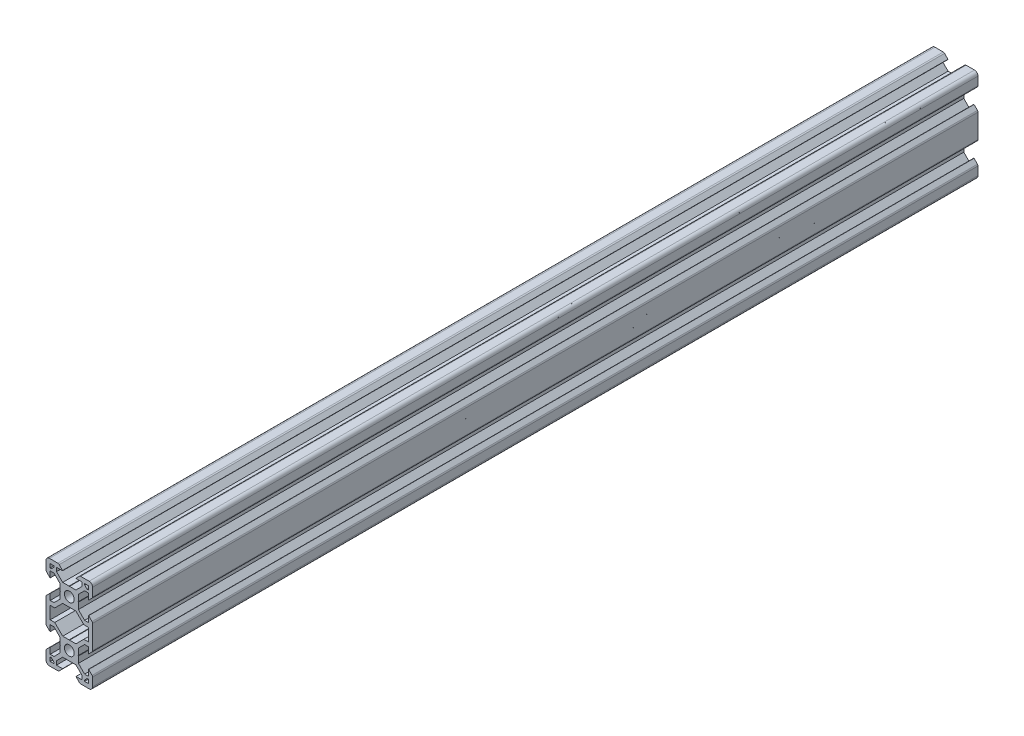
SolidWorks part; units mm, degrees
ref_plane "Front Plane" through (0, 0, 0) normal (0, 0, 1) x (1, 0, 0)
ref_plane "Top Plane" through (0, 0, 0) normal (0, 1, 0) x (1, 0, 0)
ref_plane "Right Plane" through (0, 0, 0) normal (1, 0, 0) x (0, 0, -1)
sketch "Sketch1" plane through (0, 0, 0) normal (0, 0, 1) x (1, 0, 0)
  line L0 (-8.2, 2.8875) -> (-8.2, 5.4975)
  line L3 (-4.9072, 9.9975) -> (-8.5, 9.9975)
  line L4 (-10, 4.9047) -> (-10, 8.4975)
  line L5 (-2.1, 0) -> (-3.8, 0) construction
  line L6 (0, 3.8) -> (0, 0) construction
  line L7 (-0.1, 3.9) -> (-2.8404, 3.9)
  line L8 (-3.9, 0.1) -> (-3.9, 2.8383)
  line L9 (-2.89, 8.1975) -> (-5.5, 8.1975)
  line L10 (-6.57, 8.1975) -> (-6.57, 7.6575)
  line L11 (-8.2, 6.5675) -> (-7.66, 6.5675)
  line L12 (-5.5, 8.1975) -> (-5.5, 6.5588)
  line L13 (-6.56, 5.4975) -> (-8.2, 5.4975)
  line L14 (-8.2, 8.1975) -> (-1.4852, 1.4847) construction
  line L15 (-6.56, 5.4975) -> (-3.9, 2.8383)
  line L16 (-5.5, 6.5588) -> (-2.8404, 3.9)
  line L17 (-7.66, 6.5675) -> (-6.57, 7.6575)
  line L18 (-8.7302, 7.6671) -> (-0.5302, -0.5304) construction
  line L19 (-7.6698, 8.7279) -> (0.5302, 0.5304) construction
  line L20 (-8.2, 8.1975) -> (0, 0) construction
  line L21 (-8.2, 6.5675) -> (-8.2, 8.1975)
  line L22 (-8.2, -0.0025) -> (-8.2, 8.1975) construction
  line L23 (-6.57, 8.1975) -> (-8.2, 8.1975)
  line L24 (0, 8.1975) -> (-8.2, 8.1975) construction
  line L25 (-10, -0.0025) -> (-10, 9.9975) construction
  line L26 (0, 9.9975) -> (-10, 9.9975) construction
  line L27 (-2.89, 8.3075) -> (-2.89, 8.1975)
  line L29 (-8.31, 2.8875) -> (-8.2, 2.8875)
  line L30 (-4.3486, 9.7661) -> (-2.89, 8.3075)
  line L31 (-8.31, 2.8875) -> (-9.7686, 4.3461)
  line L34 (-0.1, 3.9) -> (0, 3.8)
  line L35 (-3.9, 0.1) -> (-3.8, 0)
  line L36 (-8.2, -7.2996) -> (-6.24, -7.2996)
  line L37 (0, 0) -> (0, -10) construction
  line L38 (-0.1, -3.9) -> (-2.8404, -3.9)
  line L39 (-3.8, 0) -> (-3.9, -0.1)
  line L40 (-3.9, -0.1) -> (-3.9, -2.84)
  line L41 (-2.8404, -3.9) -> (-6.24, -7.2996)
  line L42 (-3.9, -2.84) -> (-6.56, -5.5)
  line L43 (-8.2, -2.89) -> (-8.2, -5.5)
  line L44 (-6.56, 5.4975) -> (-6.56, -5.5) construction
  line L45 (-6.56, -5.5) -> (-8.2, -5.5)
  line L46 (-0.1, -3.9) -> (0, -3.8)
  line L48 (-8.2, -2.89) -> (-8.31, -2.89)
  line L49 (-8.31, -2.89) -> (-9.7657, -4.3457)
  line L52 (-10, -10) -> (0, -10) construction
  line L53 (-8.2, -7.2996) -> (-8.2, -10)
  line L61 (-10, -4.9114) -> (-10, -10)
  arc A1 (-10, 8.4975) -> (-8.5, 9.9975) centre (-8.5, 8.4975) cw
  arc A2 (-9.7686, 4.3461) -> (-10, 4.9047) centre (-9.21, 4.9047) cw
  arc A3 (-4.3486, 9.7661) -> (-4.9072, 9.9975) centre (-4.9072, 9.2075) ccw
  arc A4 (-9.7657, -4.3457) -> (-10, -4.9114) centre (-9.2, -4.9114) ccw
  arc A6 (0, 2.1) -> (0, -2.1) centre (0, 0) ccw
  point P29 (-10, 9.9975)
  point P39 (-10, 4.5775)
  point P42 (-4.58, 9.9975)
  point P48 (-10, -4.58)
  dimension "D15" = 1.5
  dimension "D22" = 0.79
  dimension "D30" = 1.96
  dimension "D31" = 2.1
  dimension "D39" = 0.8
  dimension "D4" = 1.8
  dimension "D5" = 3.43
  dimension "D6" = 3.43
  dimension "D7" = 0.54
  dimension "D8" = 0.54
  dimension "D9" = 1.07
  dimension "D10" = 1.07
  dimension "D11" = 3.9
  dimension "D12" = 3.9
  dimension "D16" = 7.11
  dimension "D17" = 0.11
  dimension "D18" = 1.69
  dimension "D19" = 0.11
  dimension "D20" = 7.11
  dimension "D21" = 1.69
  dimension "D23" = 10
  dimension "D24" = 0.1
  dimension "D25" = 45
  dimension "D26" = 0.1
  dimension "D27" = 45
  dimension "D28" = 1.64
  dimension "D29" = 10
  dimension "D32" = 3.9
  dimension "D33" = 45
  dimension "D34" = 2.74
  dimension "D35" = 45
  dimension "D37" = 2.61
  dimension "D38" = 90
  dimension "D40" = 0.1
  dimension "D41" = 45
  dimension "D13" = 0.75
  dimension "D14" = 0.75
sketch "Sketch2" plane through (0, 0, 0) normal (0, 0, 1) x (1, 0, 0)
  line L0 (-0.1, 3.9) -> (0, 3.8) construction
  line L1 (-0.1, 3.9) -> (-2.8404, 3.9) construction
  line L2 (-5.5, 6.5588) -> (-2.8404, 3.9) construction
  line L3 (-5.5, 8.1975) -> (-5.5, 6.5588) construction
  line L4 (-2.89, 8.1975) -> (-5.5, 8.1975) construction
  line L5 (-7.66, 6.5675) -> (-6.57, 7.6575)
  line L6 (-6.57, 7.6575) -> (-6.57, 8.1975)
  line L7 (-6.57, 8.1975) -> (-8.2, 8.1975)
  line L8 (-8.2, 8.1975) -> (-8.2, 6.5675)
  line L9 (-8.2, 6.5675) -> (-7.66, 6.5675)
  line L10 (-7.66, 6.5675) -> (-6.57, 7.6575)
  line L11 (-6.57, 7.6575) -> (-6.57, 8.1975)
  line L12 (-6.57, 8.1975) -> (-8.2, 8.1975)
  line L13 (-8.2, 8.1975) -> (-8.2, 6.5675)
  line L14 (-8.2, 6.5675) -> (-7.66, 6.5675)
  line L15 (-2.89, 8.3075) -> (-2.89, 8.1975) construction
  line L16 (-4.3486, 9.7661) -> (-2.89, 8.3075) construction
  line L17 (-4.9072, 9.9975) -> (-8.5, 9.9975) construction
  line L18 (-10, 4.9047) -> (-10, 8.4975) construction
  line L19 (-8.31, 2.8875) -> (-9.7686, 4.3461) construction
  line L20 (-8.31, 2.8875) -> (-8.2, 2.8875) construction
  line L21 (-8.2, 2.8875) -> (-8.2, 5.4975) construction
  line L22 (-6.56, 5.4975) -> (-8.2, 5.4975) construction
  line L23 (-6.56, 5.4975) -> (-3.9, 2.8383) construction
  line L24 (-3.9, 0.1) -> (-3.9, 2.8383) construction
  line L25 (-3.9, 0.1) -> (-3.8, 0) construction
  line L26 (-3.8, 0) -> (-3.9, -0.1) construction
  line L27 (-3.9, -0.1) -> (-3.9, -2.84) construction
  line L28 (-3.9, -2.84) -> (-6.56, -5.5) construction
  line L29 (-6.56, -5.5) -> (-8.2, -5.5) construction
  line L30 (-8.2, -2.89) -> (-8.2, -5.5) construction
  line L31 (-8.2, -2.89) -> (-8.31, -2.89) construction
  line L32 (-8.31, -2.89) -> (-9.7657, -4.3457) construction
  line L33 (-10, -4.9114) -> (-10, -10) construction
  line L34 (-0.1, -3.9) -> (0, -3.8) construction
  line L35 (-0.1, -3.9) -> (-2.8404, -3.9) construction
  line L36 (-2.8404, -3.9) -> (-6.24, -7.2996) construction
  line L37 (-8.2, -7.2996) -> (-6.24, -7.2996) construction
  line L38 (-8.2, -7.2996) -> (-8.2, -10) construction
  line L39 (-0.1, 3.9) -> (0, 3.8)
  line L40 (-0.1, 3.9) -> (-2.8404, 3.9)
  line L41 (-5.5, 6.5588) -> (-2.8404, 3.9)
  line L42 (-5.5, 8.1975) -> (-5.5, 6.5588)
  line L43 (-2.89, 8.1975) -> (-5.5, 8.1975)
  line L44 (-2.89, 8.3075) -> (-2.89, 8.1975)
  line L45 (-4.3486, 9.7661) -> (-2.89, 8.3075)
  line L46 (-4.9072, 9.9975) -> (-8.5, 9.9975)
  line L47 (-10, 4.9047) -> (-10, 8.4975)
  line L48 (-8.31, 2.8875) -> (-9.7686, 4.3461)
  line L49 (-8.31, 2.8875) -> (-8.2, 2.8875)
  line L50 (-8.2, 2.8875) -> (-8.2, 5.4975)
  line L51 (-6.56, 5.4975) -> (-8.2, 5.4975)
  line L52 (-6.56, 5.4975) -> (-3.9, 2.8383)
  line L53 (-3.9, 0.1) -> (-3.9, 2.8383)
  line L54 (-3.9, 0.1) -> (-3.8, 0)
  line L55 (-3.8, 0) -> (-3.9, -0.1)
  line L56 (-3.9, -0.1) -> (-3.9, -2.84)
  line L57 (-3.9, -2.84) -> (-6.56, -5.5)
  line L58 (-6.56, -5.5) -> (-8.2, -5.5)
  line L59 (-8.2, -2.89) -> (-8.2, -5.5)
  line L60 (-8.2, -2.89) -> (-8.31, -2.89)
  line L61 (-8.31, -2.89) -> (-9.7657, -4.3457)
  line L62 (-10, -4.9114) -> (-10, -15.0886)
  line L63 (-0.1, -3.9) -> (0, -3.8)
  line L64 (-0.1, -3.9) -> (-2.8404, -3.9)
  line L65 (-2.8404, -3.9) -> (-6.24, -7.2996)
  line L66 (-8.2, -7.2996) -> (-6.24, -7.2996)
  line L67 (-8.2, -7.2996) -> (-8.2, -12.7004)
  line L68 (0, 0) -> (0, -10) construction
  line L69 (-10, -10) -> (0, -10) construction
  line L70 (0, 0) -> (0, -20) construction
  line L71 (-10, -10) -> (10, -10) construction
  line L72 (8.2, -7.2996) -> (8.2, -12.7004)
  line L73 (8.2, -7.2996) -> (6.24, -7.2996)
  line L74 (2.8404, -3.9) -> (6.24, -7.2996)
  line L75 (0.1, -3.9) -> (2.8404, -3.9)
  line L76 (0.1, -3.9) -> (0, -3.8)
  line L77 (10, -4.9114) -> (10, -15.0886)
  line L78 (8.31, -2.89) -> (9.7657, -4.3457)
  line L79 (8.2, -2.89) -> (8.31, -2.89)
  line L80 (8.2, -2.89) -> (8.2, -5.5)
  line L81 (6.56, -5.5) -> (8.2, -5.5)
  line L82 (3.9, -2.84) -> (6.56, -5.5)
  line L83 (3.9, -0.1) -> (3.9, -2.84)
  line L84 (3.8, 0) -> (3.9, -0.1)
  line L85 (3.9, 0.1) -> (3.8, 0)
  line L86 (3.9, 0.1) -> (3.9, 2.8383)
  line L87 (6.56, 5.4975) -> (3.9, 2.8383)
  line L88 (6.56, 5.4975) -> (8.2, 5.4975)
  line L89 (8.2, 2.8875) -> (8.2, 5.4975)
  line L90 (8.31, 2.8875) -> (8.2, 2.8875)
  line L91 (8.31, 2.8875) -> (9.7686, 4.3461)
  line L92 (10, 4.9047) -> (10, 8.4975)
  line L93 (4.9072, 9.9975) -> (8.5, 9.9975)
  line L94 (4.3486, 9.7661) -> (2.89, 8.3075)
  line L95 (2.89, 8.3075) -> (2.89, 8.1975)
  line L96 (2.89, 8.1975) -> (5.5, 8.1975)
  line L97 (5.5, 8.1975) -> (5.5, 6.5588)
  line L98 (5.5, 6.5588) -> (2.8404, 3.9)
  line L99 (0.1, 3.9) -> (2.8404, 3.9)
  line L100 (0.1, 3.9) -> (0, 3.8)
  line L101 (8.2, 6.5675) -> (7.66, 6.5675)
  line L102 (8.2, 8.1975) -> (8.2, 6.5675)
  line L103 (6.57, 8.1975) -> (8.2, 8.1975)
  line L104 (6.57, 7.6575) -> (6.57, 8.1975)
  line L105 (7.66, 6.5675) -> (6.57, 7.6575)
  line L106 (7.66, -26.5675) -> (6.57, -27.6575)
  line L107 (6.57, -27.6575) -> (6.57, -28.1975)
  line L108 (6.57, -28.1975) -> (8.2, -28.1975)
  line L109 (8.2, -28.1975) -> (8.2, -26.5675)
  line L110 (8.2, -26.5675) -> (7.66, -26.5675)
  line L111 (0.1, -23.9) -> (0, -23.8)
  line L112 (0.1, -23.9) -> (2.8404, -23.9)
  line L113 (5.5, -26.5588) -> (2.8404, -23.9)
  line L114 (5.5, -28.1975) -> (5.5, -26.5588)
  line L115 (2.89, -28.1975) -> (5.5, -28.1975)
  line L116 (2.89, -28.3075) -> (2.89, -28.1975)
  line L117 (4.3486, -29.7661) -> (2.89, -28.3075)
  line L118 (4.9072, -29.9975) -> (8.5, -29.9975)
  line L119 (10, -24.9047) -> (10, -28.4975)
  line L120 (8.31, -22.8875) -> (9.7686, -24.3461)
  line L121 (8.31, -22.8875) -> (8.2, -22.8875)
  line L122 (8.2, -22.8875) -> (8.2, -25.4975)
  line L123 (6.56, -25.4975) -> (8.2, -25.4975)
  line L124 (6.56, -25.4975) -> (3.9, -22.8383)
  line L125 (3.9, -20.1) -> (3.9, -22.8383)
  line L126 (3.9, -20.1) -> (3.8, -20)
  line L127 (3.8, -20) -> (3.9, -19.9)
  line L128 (3.9, -19.9) -> (3.9, -17.16)
  line L129 (3.9, -17.16) -> (6.56, -14.5)
  line L130 (6.56, -14.5) -> (8.2, -14.5)
  line L131 (8.2, -17.11) -> (8.2, -14.5)
  line L132 (8.2, -17.11) -> (8.31, -17.11)
  line L133 (8.31, -17.11) -> (9.7657, -15.6543)
  line L134 (0.1, -16.1) -> (0, -16.2)
  line L135 (0.1, -16.1) -> (2.8404, -16.1)
  line L136 (2.8404, -16.1) -> (6.24, -12.7004)
  line L137 (8.2, -12.7004) -> (6.24, -12.7004)
  line L138 (-8.2, -12.7004) -> (-6.24, -12.7004)
  line L139 (-2.8404, -16.1) -> (-6.24, -12.7004)
  line L140 (-0.1, -16.1) -> (-2.8404, -16.1)
  line L141 (-0.1, -16.1) -> (0, -16.2)
  line L142 (-8.31, -17.11) -> (-9.7657, -15.6543)
  line L143 (-8.2, -17.11) -> (-8.31, -17.11)
  line L144 (-8.2, -17.11) -> (-8.2, -14.5)
  line L145 (-6.56, -14.5) -> (-8.2, -14.5)
  line L146 (-3.9, -17.16) -> (-6.56, -14.5)
  line L147 (-3.9, -19.9) -> (-3.9, -17.16)
  line L148 (-3.8, -20) -> (-3.9, -19.9)
  line L149 (-3.9, -20.1) -> (-3.8, -20)
  line L150 (-3.9, -20.1) -> (-3.9, -22.8383)
  line L151 (-6.56, -25.4975) -> (-3.9, -22.8383)
  line L152 (-6.56, -25.4975) -> (-8.2, -25.4975)
  line L153 (-8.2, -22.8875) -> (-8.2, -25.4975)
  line L154 (-8.31, -22.8875) -> (-8.2, -22.8875)
  line L155 (-8.31, -22.8875) -> (-9.7686, -24.3461)
  line L156 (-10, -24.9047) -> (-10, -28.4975)
  line L157 (-4.9072, -29.9975) -> (-8.5, -29.9975)
  line L158 (-4.3486, -29.7661) -> (-2.89, -28.3075)
  line L159 (-2.89, -28.3075) -> (-2.89, -28.1975)
  line L160 (-2.89, -28.1975) -> (-5.5, -28.1975)
  line L161 (-5.5, -28.1975) -> (-5.5, -26.5588)
  line L162 (-5.5, -26.5588) -> (-2.8404, -23.9)
  line L163 (-0.1, -23.9) -> (-2.8404, -23.9)
  line L164 (-0.1, -23.9) -> (0, -23.8)
  line L165 (-8.2, -26.5675) -> (-7.66, -26.5675)
  line L166 (-8.2, -28.1975) -> (-8.2, -26.5675)
  line L167 (-6.57, -28.1975) -> (-8.2, -28.1975)
  line L168 (-6.57, -27.6575) -> (-6.57, -28.1975)
  line L169 (-7.66, -26.5675) -> (-6.57, -27.6575)
  arc A0 (0, 2.1) -> (0, -2.1) centre (0, 0) ccw construction
  arc A1 (-4.3486, 9.7661) -> (-4.9072, 9.9975) centre (-4.9072, 9.2075) ccw construction
  arc A2 (-8.5, 9.9975) -> (-10, 8.4975) centre (-8.5, 8.4975) ccw construction
  arc A3 (-10, 4.9047) -> (-9.7686, 4.3461) centre (-9.21, 4.9047) ccw construction
  arc A4 (-9.7657, -4.3457) -> (-10, -4.9114) centre (-9.2, -4.9114) ccw construction
  circle A5 centre (0, 0) radius 2.1
  arc A6 (-4.3486, 9.7661) -> (-4.9072, 9.9975) centre (-4.9072, 9.2075) ccw
  arc A7 (-8.5, 9.9975) -> (-10, 8.4975) centre (-8.5, 8.4975) ccw
  arc A8 (-10, 4.9047) -> (-9.7686, 4.3461) centre (-9.21, 4.9047) ccw
  arc A9 (-9.7657, -4.3457) -> (-10, -4.9114) centre (-9.2, -4.9114) ccw
  arc A10 (9.7657, -4.3457) -> (10, -4.9114) centre (9.2, -4.9114) cw
  arc A11 (10, 4.9047) -> (9.7686, 4.3461) centre (9.21, 4.9047) cw
  arc A12 (8.5, 9.9975) -> (10, 8.4975) centre (8.5, 8.4975) cw
  arc A13 (4.3486, 9.7661) -> (4.9072, 9.9975) centre (4.9072, 9.2075) cw
  arc A14 (4.3486, -29.7661) -> (4.9072, -29.9975) centre (4.9072, -29.2075) ccw
  arc A15 (8.5, -29.9975) -> (10, -28.4975) centre (8.5, -28.4975) ccw
  arc A16 (10, -24.9047) -> (9.7686, -24.3461) centre (9.21, -24.9047) ccw
  arc A17 (9.7657, -15.6543) -> (10, -15.0886) centre (9.2, -15.0886) ccw
  arc A18 (-9.7657, -15.6543) -> (-10, -15.0886) centre (-9.2, -15.0886) cw
  arc A19 (-10, -24.9047) -> (-9.7686, -24.3461) centre (-9.21, -24.9047) cw
  arc A20 (-8.5, -29.9975) -> (-10, -28.4975) centre (-8.5, -28.4975) cw
  arc A21 (-4.3486, -29.7661) -> (-4.9072, -29.9975) centre (-4.9072, -29.2075) cw
  circle A22 centre (0, -20) radius 2.1
  point P147 (8.2, -10)
  dimension "D1" = 0
extrude "Boss-Extrude1" add sketch "Sketch2" against normal blind 380
